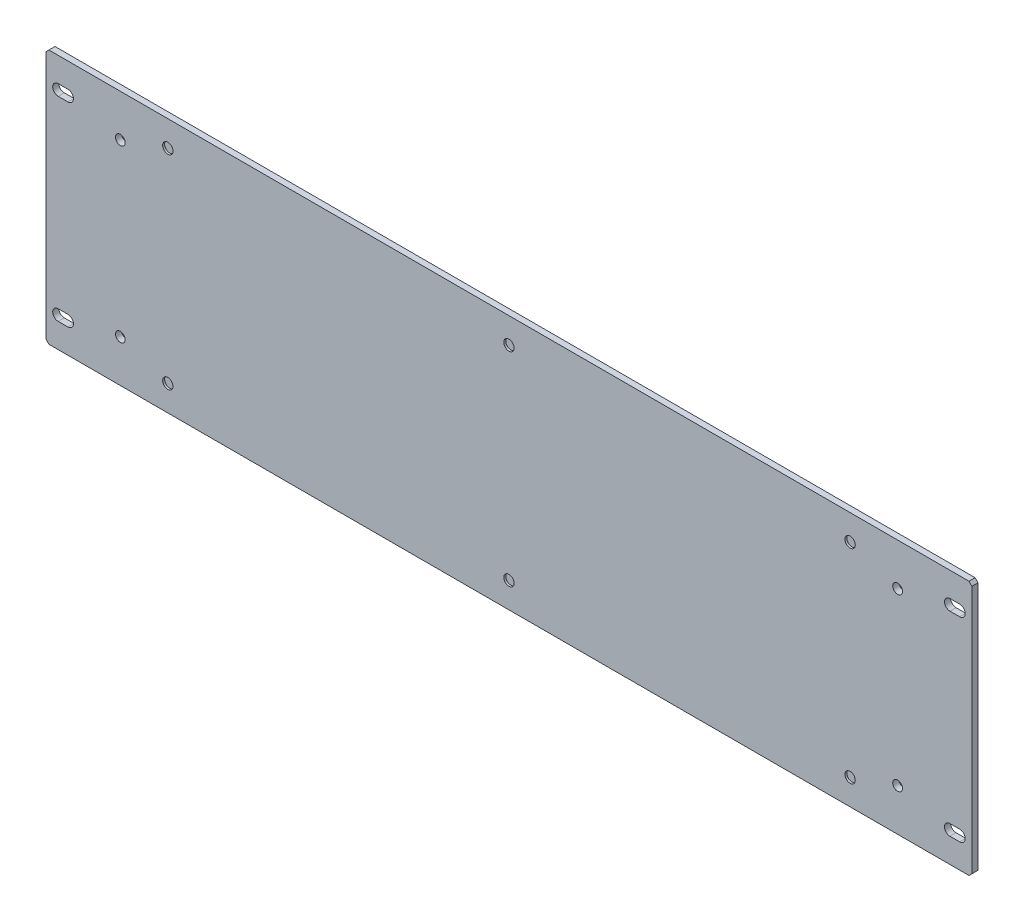
SolidWorks part; units mm, degrees
material "Ductile Iron"
ref_plane "Front Plane" through (0, 0, 0) normal (0, 0, 1) x (1, 0, 0)
ref_plane "Top Plane" through (0, 0, 0) normal (0, 1, 0) x (1, 0, 0)
ref_plane "Right Plane" through (0, 0, 0) normal (1, 0, 0) x (0, 0, -1)
sketch "Sketch1" plane through (0, 0, 0) normal (0, 0, 1) x (1, 0, 0)
  line L0 (-57.2704, -1.8182) -> (-52.1904, -1.8182) construction
  line L1 (-63.6204, 13.8028) -> (418.9796, 13.8028)
  line L2 (-63.6204, 13.8028) -> (-63.6204, -119.0392)
  line L3 (-63.6204, -119.0392) -> (418.9796, -119.0392)
  line L4 (418.9796, 13.8028) -> (418.9796, -119.0392)
  line L5 (-57.2704, 1.0393) -> (-52.1904, 1.0393)
  line L6 (-57.2704, -4.6757) -> (-52.1904, -4.6757)
  line L7 (407.5496, -1.8182) -> (412.6296, -1.8182) construction
  line L8 (407.5496, 1.0393) -> (412.6296, 1.0393)
  line L9 (407.5496, -4.6757) -> (412.6296, -4.6757)
  line L10 (-57.2704, -103.4182) -> (-52.1904, -103.4182) construction
  line L11 (-57.2704, -100.5607) -> (-52.1904, -100.5607)
  line L12 (-57.2704, -106.2757) -> (-52.1904, -106.2757)
  line L13 (407.5496, -103.4182) -> (412.6296, -103.4182) construction
  line L14 (407.5496, -100.5607) -> (412.6296, -100.5607)
  line L15 (407.5496, -106.2757) -> (412.6296, -106.2757)
  circle A0 centre (-24.8854, -8.1682) radius 2.54
  circle A1 centre (-24.8854, -97.0682) radius 2.54
  circle A2 centre (380.2446, -97.0682) radius 2.54
  circle A3 centre (380.2446, -8.1682) radius 2.54
  arc A4 (-57.2704, 1.0393) -> (-57.2704, -4.6757) centre (-57.2704, -1.8182) ccw
  arc A5 (-52.1904, -4.6757) -> (-52.1904, 1.0393) centre (-52.1904, -1.8182) ccw
  arc A6 (407.5496, 1.0393) -> (407.5496, -4.6757) centre (407.5496, -1.8182) ccw
  arc A7 (412.6296, -4.6757) -> (412.6296, 1.0393) centre (412.6296, -1.8182) ccw
  arc A8 (-57.2704, -100.5607) -> (-57.2704, -106.2757) centre (-57.2704, -103.4182) ccw
  arc A9 (-52.1904, -106.2757) -> (-52.1904, -100.5607) centre (-52.1904, -103.4182) ccw
  arc A10 (407.5496, -100.5607) -> (407.5496, -106.2757) centre (407.5496, -103.4182) ccw
  arc A11 (412.6296, -106.2757) -> (412.6296, -100.5607) centre (412.6296, -103.4182) ccw
  point P14 (-54.7304, -1.8182)
  point P23 (410.0896, -1.8182)
  point P30 (-54.7304, -103.4182)
  point P37 (410.0896, -103.4182)
  point P42 (0, 0)
  point P43 (0, 0)
  dimension "D3" = 5.08
  dimension "D4" = 5.08
  dimension "D5" = 2
  dimension "D6" = 5.08
  dimension "D18" = 2.8575
  dimension "D8" = 21.971
  dimension "D10" = 15.621
  dimension "D11" = 405.13
  dimension "D9" = 38.735
  dimension "D15" = 88.9
  dimension "D1" = 482.6
  dimension "D2" = 132.842
  dimension "D7" = 38.735
  dimension "D12" = 8.89
  dimension "D14" = 8.89
  dimension "D16" = 2
  dimension "D13" = 2
extrude "Boss-Extrude1" add sketch "Sketch1" along normal blind 3.175
sketch "Sketch2" plane through (0, 0, 3.175) normal (0, 0, 1) x (1, 0, 0)
  line L0 (418.9796, 13.8028) -> (-63.6204, 13.8028) construction
  line L1 (-19.8054, 9.6118) -> (375.1646, 9.6118)
  line L2 (-19.8054, 9.6118) -> (-19.8054, 8.0878)
  line L3 (-19.8054, 8.0878) -> (375.1646, 8.0878)
  line L4 (375.1646, 9.6118) -> (375.1646, 8.0878)
  line L5 (-63.6204, 13.8028) -> (-63.6204, -119.0392) construction
  line L6 (418.9796, -119.0392) -> (418.9796, 13.8028) construction
  line L9 (-19.8054, -25.9482) -> (-19.8054, -24.4242)
  line L10 (375.1646, -25.9482) -> (375.1646, -24.4242)
  line L11 (-19.8054, -24.4242) -> (375.1646, -24.4242)
  line L12 (-19.8054, -25.9482) -> (375.1646, -25.9482)
  dimension "D1" = 4.191
  dimension "D2" = 1.524
  dimension "D3" = 43.815
  dimension "D4" = 43.815
  dimension "D5" = 35.56
  dimension "D6" = 43.815
  dimension "D7" = 43.815
  dimension "D8" = 1.524
extrude "Boss-Extrude2" [suppressed] add sketch "Sketch2" along normal blind 10.16
sketch "Sketch3" [suppressed] plane through (0, 98.5118, 0) normal (0, 1, 0) x (-1, 0, 0)
  line L0 (61.8424, 3.175) -> (61.8424, 0) construction
  line L2 (-376.9426, 3.175) -> (18.0274, 3.175) construction
  circle A0 centre (11.0424, 10.795) radius 1.27
  circle A1 centre (-115.9576, 10.795) radius 1.27
  circle A2 centre (-242.9576, 10.795) radius 1.27
  circle A3 centre (-369.9576, 10.795) radius 1.27
  dimension "D1" = 2.54
  dimension "D4" = 7.62
  dimension "D2" = 50.8
  dimension "D3" = 4
extrude "Cut-Extrude1" [suppressed] cut sketch "Sketch3" against normal through all
sketch "Sketch5" plane through (0, 0, 3.175) normal (0, 0, 1) x (1, 0, 0)
  line L1 (-63.6204, 13.8028) -> (-63.6204, -119.0392) construction
  line L3 (418.9796, 13.8028) -> (-63.6204, 13.8028) construction
  circle A0 centre (-0.1204, 0.4678) radius 2.7051
  circle A1 centre (177.6796, 0.4678) radius 2.7051
  circle A2 centre (355.4796, 0.4678) radius 2.7051
  circle A3 centre (177.6796, -105.7042) radius 2.7051
  circle A4 centre (355.4796, -105.7042) radius 2.7051
  circle A5 centre (-0.1204, -105.7042) radius 2.7051
  dimension "D1" = 5.4102
  dimension "D2" = 106.172
  dimension "D3" = 63.5
  dimension "D6" = 13.335
  dimension "D7" = 177.8
  dimension "D4" = 3
  dimension "D5" = 2
extrude "Cut-Extrude2" cut sketch "Sketch5" against normal blind 1.0414
chamfer "Chamfer1" distance 1.524 angle 45 4 edges at (-63.6204, -119.0392, 1.5875) (418.9796, -119.0392, 1.5875) (418.9796, 13.8028, 1.5875) (-63.6204, 13.8028, 1.5875)
